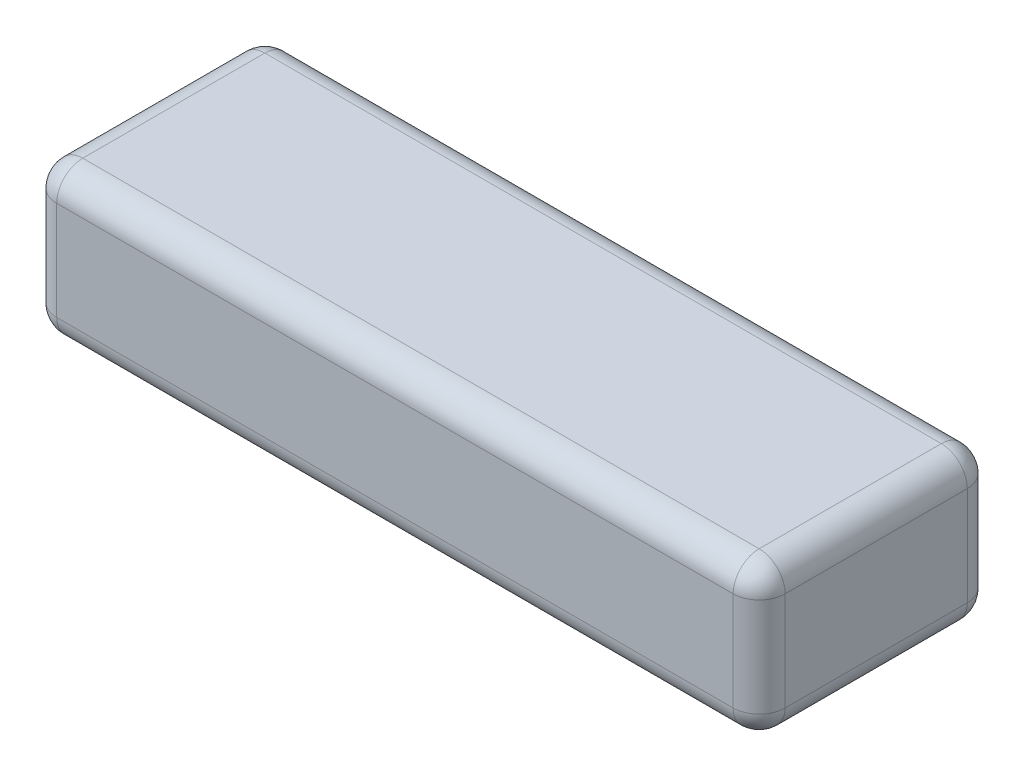
SolidWorks part; units mm, degrees
material "Thornel Mat VMA"
ref_plane "Front Plane" through (0, 0, 0) normal (0, 0, 1) x (1, 0, 0)
ref_plane "Top Plane" through (0, 0, 0) normal (0, 1, 0) x (1, 0, 0)
ref_plane "Right Plane" through (0, 0, 0) normal (1, 0, 0) x (0, 0, -1)
sketch "Sketch2" plane through (0, 0, 0) normal (0, 1, 0) x (1, 0, 0)
  line L1 (70, -22.5) -> (-70, -22.5)
  line L2 (70, -22.5) -> (70, 22.5)
  line L3 (70, 22.5) -> (-70, 22.5)
  line L4 (-70, -22.5) -> (-70, 22.5)
  line L5 (70, -22.5) -> (-70, 22.5) construction
  line L6 (70, 22.5) -> (-70, -22.5) construction
  point P0 (0, 0)
  dimension "D1" = 140
  dimension "D2" = 45
extrude "Boss-Extrude1" add sketch "Sketch2" along normal blind 29
fillet "Fillet1" radius 5 12 edges at (0, 0, -22.5) (-70, 14.5, -22.5) (-70, 0, 0) (70, 14.5, -22.5) (70, 0, 0) (-70, 14.5, 22.5) (70, 14.5, 22.5) (0, 0, 22.5) (0, 29, -22.5) (70, 29, 0) (0, 29, 22.5) (-70, 29, 0)
